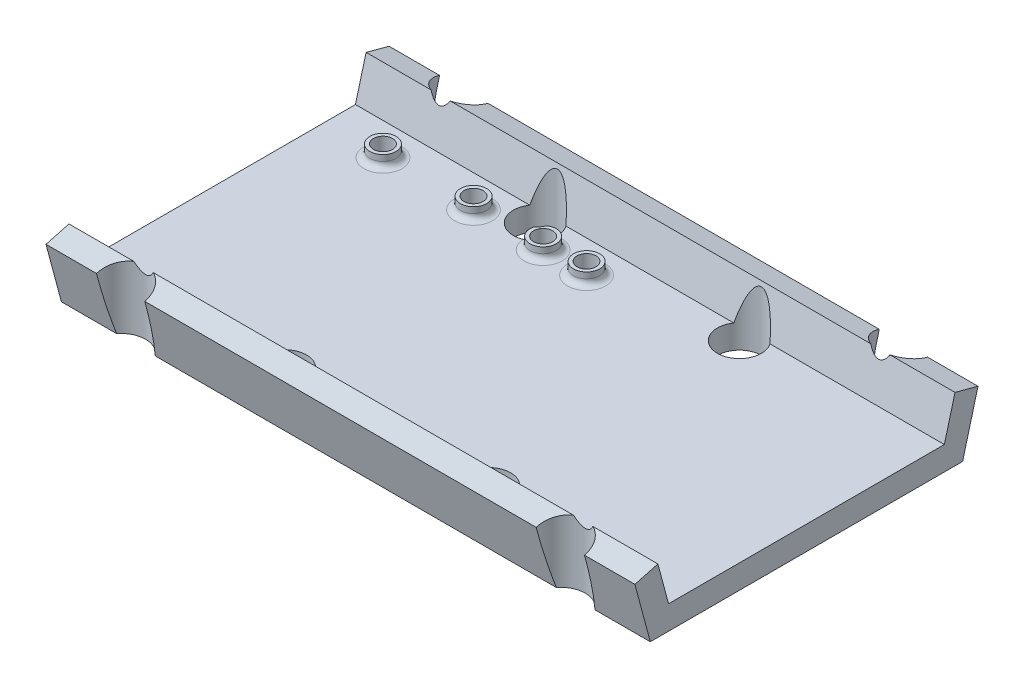
SolidWorks part; units mm, degrees
ref_plane "Front Plane" through (0, 0, 0) normal (0, 0, 1) x (1, 0, 0)
ref_plane "Top Plane" through (0, 0, 0) normal (0, 1, 0) x (1, 0, 0)
ref_plane "Right Plane" through (0, 0, 0) normal (1, 0, 0) x (0, 0, -1)
sketch "Sketch2" plane through (0, 0, 0) normal (0, 1, 0) x (1, 0, 0)
  line L0 (-164.1399, 0) -> (192.7344, 0) construction
  line L1 (49.5, 26.25) -> (-49.5, 26.25)
  line L2 (49.5, 26.25) -> (49.5, -26.25)
  line L3 (49.5, -26.25) -> (-49.5, -26.25)
  line L4 (-49.5, 26.25) -> (-49.5, -26.25)
  line L5 (49.5, 26.25) -> (-49.5, -26.25) construction
  line L6 (49.5, -26.25) -> (-49.5, 26.25) construction
  line L7 (0, 113.4496) -> (0, -113.4496) construction
  line L8 (0, 21.082) -> (-25.9231, 21.082) construction
  line L9 (0, 21.082) -> (25.9231, 21.082) construction
  line L10 (-25.9231, 0) -> (-25.9231, 21.082) construction
  line L11 (-25.9231, 0) -> (-25.9231, -21.082) construction
  line L12 (-25.9231, -21.082) -> (25.9231, -21.082) construction
  point P0 (0, 0)
  dimension "D1" = 21.082
  dimension "D2" = 21.082
  dimension "D3" = 52.5
  dimension "D4" = 99
  dimension "D5" = 25.9231
extrude "FlatTemplate" add sketch "Sketch2" along normal blind 4
sketch "TopOuterHoles" plane through (0, 4, 0) normal (0, 1, 0) x (1, 0, 0)
  line L0 (0, 0) -> (-36.96, 0) construction
  line L1 (0, 0) -> (36.96, 0) construction
  line L2 (0, 0) -> (0, 28.7) construction
  line L3 (0, 0) -> (0, -28.7) construction
  circle A0 centre (-36.96, 28.7) radius 4.064
  circle A1 centre (36.96, 28.7) radius 4.064
  circle A2 centre (36.96, -28.7) radius 4.064
  circle A3 centre (-36.96, -28.7) radius 4.064
sketch "Sketch4" plane through (49.5, 0, 0) normal (1, 0, 0) x (0, 0, -1)
  line L0 (-26.25, 0) -> (-28.8382, 9.6593)
  line L1 (-26.25, 0) -> (-22.3863, 1.0353)
  line L2 (-28.8382, 9.6593) -> (-24.9745, 10.6945)
  line L3 (-22.3863, 1.0353) -> (-24.9745, 10.6945)
  line L5 (0, 4) -> (-28.7, 4) construction
  line L6 (26.25, 0) -> (28.8382, 9.6593)
  line L7 (26.25, 0) -> (22.3863, 1.0353)
  line L8 (28.8382, 9.6593) -> (24.9745, 10.6945)
  line L9 (22.3863, 1.0353) -> (24.9745, 10.6945)
  line L10 (0, 4) -> (28.7, 4) construction
  dimension "D1" = 75
  dimension "D2" = 75
extrude "SideWalls" add sketch "Sketch4" against normal through all
sketch "InnerHoles" plane through (0, 4, 0) normal (0, 1, 0) x (1, 0, 0)
  line L0 (-190.0894, 0) -> (166.7849, 0) construction
  line L1 (17.15, 21.082) -> (17.15, -21.082) construction
  line L5 (49.5, 26.25) -> (-49.5, -26.25) construction
  line L6 (49.5, -26.25) -> (-49.5, 26.25) construction
  line L7 (0, 127.4205) -> (0, -99.4788) construction
  line L8 (0, 21.082) -> (-17.15, 21.082) construction
  line L9 (0, 21.082) -> (17.15, 21.082) construction
  line L10 (-17.15, 0) -> (-17.15, 21.082) construction
  line L11 (-17.15, 0) -> (-17.15, -21.082) construction
  line L12 (-17.15, -21.082) -> (17.15, -21.082) construction
  circle A0 centre (-17.15, 21.082) radius 1
  circle A1 centre (17.15, 21.082) radius 1
  circle A2 centre (17.15, -21.082) radius 1
  circle A3 centre (-17.15, -21.082) radius 1
  point P0 (0, 0)
  dimension "D6" = 2
  dimension "D1" = 21.082
  dimension "D2" = 21.082
  dimension "D3" = 52.5
  dimension "D4" = 99
  dimension "D5" = 17.15
extrude "InnerHolesCut" cut sketch "InnerHoles" against normal through all both and the other way through all
extrude "OuterHolesCut" cut sketch "TopOuterHoles" against normal through all both and the other way through all
sketch "TargetHoles" plane through (0, 4, 0) normal (0, 1, 0) x (1, 0, 0)
  line L0 (-17.15, 21.082) -> (-24.25, 21.082) construction
  line L1 (-24.25, 21.082) -> (-39.45, 21.082) construction
  line L2 (-17.15, 21.082) -> (-12.55, 21.082) construction
  line L3 (-12.55, 21.082) -> (-5.25, 21.082) construction
  line L4 (-24.25, 21.082) -> (-24.25, 17.782) construction
  line L5 (-39.45, 17.7578) -> (-39.45, 21.082) construction
  line L6 (-5.25, 21.082) -> (-5.25, 17.782) construction
  line L7 (-12.55, 21.082) -> (-12.55, 17.782) construction
  line L8 (-24.25, 17.782) -> (-12.55, 17.782) construction
  line L9 (-12.55, 17.782) -> (-5.25, 17.782) construction
  circle A0 centre (-5.25, 17.782) radius 2.2
  circle A1 centre (-12.55, 17.782) radius 2.2
  circle A2 centre (-24.25, 17.782) radius 2.2
  circle A3 centre (-39.45, 17.7578) radius 2.2
  dimension "D1" = 7.1
  dimension "D2" = 15.2
  dimension "D3" = 4.6
  dimension "D4" = 7.3
  dimension "D5" = 3.3
extrude "TargetHoleSupports" add sketch "TargetHoles" along normal blind 2
fillet "TargetHoleFillets" radius 1 4 edges at (-39.45, 4, -19.9578) (-24.25, 4, -19.982) (-12.55, 4, -19.982) (-5.25, 4, -19.982)
sketch "Sketch10" plane through (0, 4, 0) normal (0, 1, 0) x (1, 0, 0)
  circle A0 centre (-5.25, 17.782) radius 1.6
  circle A1 centre (-12.55, 17.782) radius 1.6
  circle A2 centre (-24.25, 17.782) radius 1.6
  circle A3 centre (-39.45, 17.7578) radius 1.6
extrude "TargetHoleHoles" cut sketch "Sketch10" against normal through all both and the other way through all
sketch "Sketch11" plane through (0, 4, 0) normal (0, 1, 0) x (1, 0, 0)
  circle A0 centre (17.15, 21.082) radius 3.7
  circle A1 centre (-17.15, 21.082) radius 3.7
  circle A2 centre (-17.15, -21.082) radius 3.7
  circle A4 centre (17.15, -21.082) radius 3.7
  dimension "D1" = 7.4
extrude "InnerHolesReCut" cut sketch "Sketch11" against normal through all both and the other way through all
